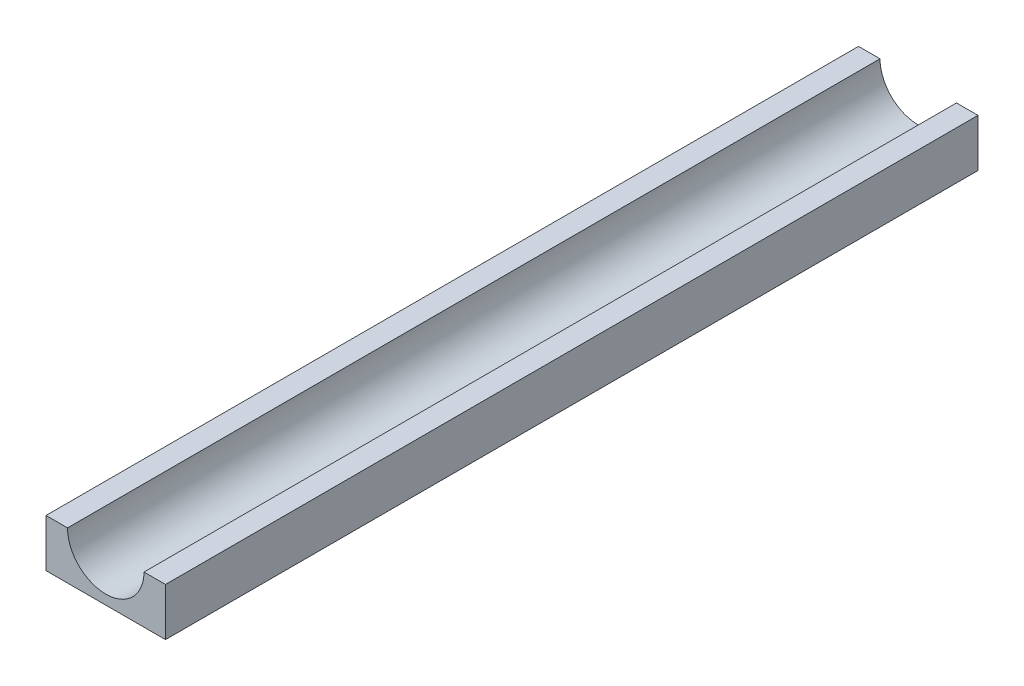
SolidWorks part; units mm, degrees
ref_plane "Front Plane" through (0, 0, 0) normal (0, 0, 1) x (1, 0, 0)
ref_plane "Top Plane" through (0, 0, 0) normal (0, 1, 0) x (1, 0, 0)
ref_plane "Right Plane" through (0, 0, 0) normal (1, 0, 0) x (0, 0, -1)
sketch "Sketch2" plane through (0, 0, 0) normal (0, 0, 1) x (1, 0, 0)
  line L7 (12.5, 5) -> (-12.5, 5)
  line L8 (12.5, 5) -> (12.5, -5)
  line L9 (12.5, -5) -> (-12.5, -5)
  line L10 (-12.5, 5) -> (-12.5, -5)
  line L11 (12.5, 5) -> (-12.5, -5) construction
  line L12 (12.5, -5) -> (-12.5, 5) construction
  point P0 (0, -1.1681)
  point P1 (13, 0)
  point P3 (0, -1.1681)
  point P5 (0, 0)
  point P7 (7.6504, 2.339)
  dimension "D1" = 25
  dimension "D2" = 10
extrude "Boss-Extrude1" add sketch "Sketch2" along normal blind 170
sketch "Sketch3" plane through (0, 0, 0) normal (0, 0, -1) x (-1, 0, 0)
  line L0 (-12.5, 5) -> (12.5, 5) construction
  line L1 (-8, 5) -> (8, 5)
  arc A0 (8, 5) -> (-8, 5) centre (0, 5) cw
  dimension "D1" = 8
extrude "Cut-Extrude1" cut sketch "Sketch3" against normal up to surface (170 mm away) up to face at (0, 0, 170)
sketch "Sketch4" [suppressed] plane through (0, 0, 0) normal (0, 0, -1) x (-1, 0, 0)
  line L0 (-12.5, 5) -> (12.5, 5) construction
  line L1 (-9.5, 5) -> (9.5, 5)
  arc A0 (9.5, 5) -> (-9.5, 5) centre (0, 5) cw
  dimension "D1" = 9.5
extrude "Cut-Extrude2" [suppressed] cut sketch "Sketch4" against normal up to surface (170 mm away)
sketch "Sketch5" [suppressed] plane through (0, 0, 0) normal (0, 0, -1) x (-1, 0, 0)
  line L0 (-12.5, -5) -> (-12.5, -7)
  line L1 (-12.5, -7) -> (12.5, -7)
  line L2 (12.5, -7) -> (12.5, -5)
  line L3 (12.5, -5) -> (-12.5, -5)
  dimension "D1" = 2
extrude "Boss-Extrude2" [suppressed] add sketch "Sketch5" against normal up to surface (170 mm away)
sketch "Sketch6" [suppressed] plane through (0, 0, 0) normal (0, 0, -1) x (-1, 0, 0)
  line L0 (-12.5, 5) -> (12.5, 5) construction
  line L1 (-11, 5) -> (11, 5)
  arc A0 (11, 5) -> (-11, 5) centre (0, 5) cw
  dimension "D1" = 11
extrude "Cut-Extrude3" [suppressed] cut sketch "Sketch6" against normal up to surface (170 mm away)
sketch "Sketch7" [suppressed] plane through (0, 0, 0) normal (0, 0, -1) x (-1, 0, 0)
  line L0 (-12.5, -7) -> (-12.5, -9)
  line L1 (-12.5, -9) -> (12.5, -9)
  line L2 (12.5, -9) -> (12.5, -7)
  line L3 (12.5, -7) -> (-12.5, -7)
  dimension "D1" = 2
extrude "Boss-Extrude3" [suppressed] add sketch "Sketch7" against normal up to surface (170 mm away)
